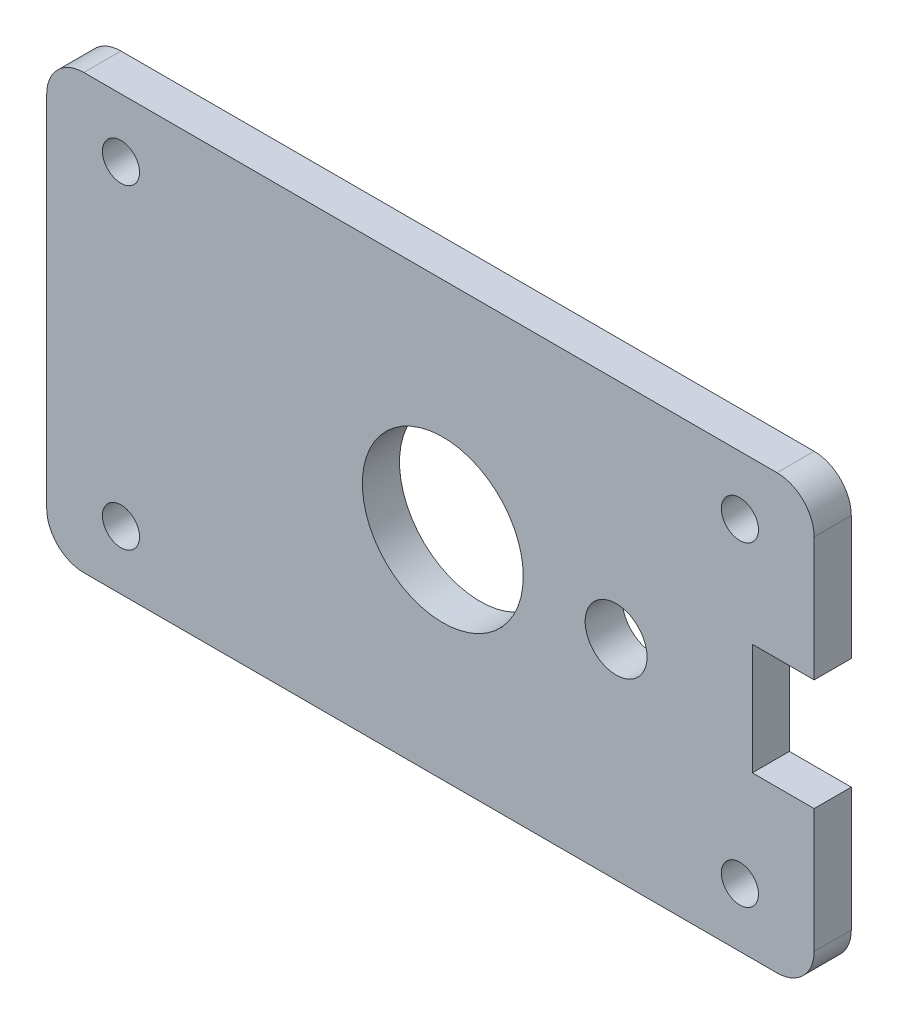
SolidWorks part; units mm, degrees
ref_plane "Front Plane" through (0, 0, 0) normal (0, 0, 1) x (1, 0, 0)
ref_plane "Top Plane" through (0, 0, 0) normal (0, 1, 0) x (1, 0, 0)
ref_plane "Right Plane" through (0, 0, 0) normal (1, 0, 0) x (0, 0, -1)
sketch "Sketch1" plane through (0, 0, 0) normal (0, 0, 1) x (1, 0, 0)
  line L0 (31, 4.5) -> (26, 4.5)
  line L1 (-28, 17.5) -> (28, 17.5)
  line L2 (-31, 14.5) -> (-31, -14.5)
  line L3 (-28, -17.5) -> (28, -17.5)
  line L5 (0, -17.5) -> (0, 17.5) construction
  line L6 (31, 4.5) -> (-31, 4.5) construction
  line L7 (26, 4.5) -> (26, -4.5)
  line L8 (-31, -4.5) -> (31, -4.5) construction
  line L9 (26, -4.5) -> (31, -4.5)
  line L10 (31, 14.5) -> (31, 4.5)
  line L11 (31, -4.5) -> (31, -14.5)
  circle A1 centre (15, -0.6545) radius 2.5
  circle A2 centre (1, 0) radius 6.5
  arc A3 (28, -17.5) -> (31, -14.5) centre (28, -14.5) ccw
  arc A4 (-31, -14.5) -> (-28, -17.5) centre (-28, -14.5) ccw
  arc A5 (28, 17.5) -> (31, 14.5) centre (28, 14.5) cw
  arc A6 (-28, 17.5) -> (-31, 14.5) centre (-28, 14.5) ccw
  circle A7 centre (-25, 12.75) radius 1.5
  circle A8 centre (25, 12.75) radius 1.5
  circle A9 centre (25, -12.75) radius 1.5
  circle A10 centre (-25, -12.75) radius 1.5
  point P0 (0, 0)
  point P18 (31, -17.5)
  point P21 (-31, -17.5)
  point P27 (-31, 17.5)
  dimension "D3" = 13
  dimension "D4" = 5
  dimension "D6" = 3
  dimension "D1" = 62
  dimension "D2" = 35
  dimension "D5" = 5
extrude "Boss-Extrude1" add sketch "Sketch1" along normal blind 3
